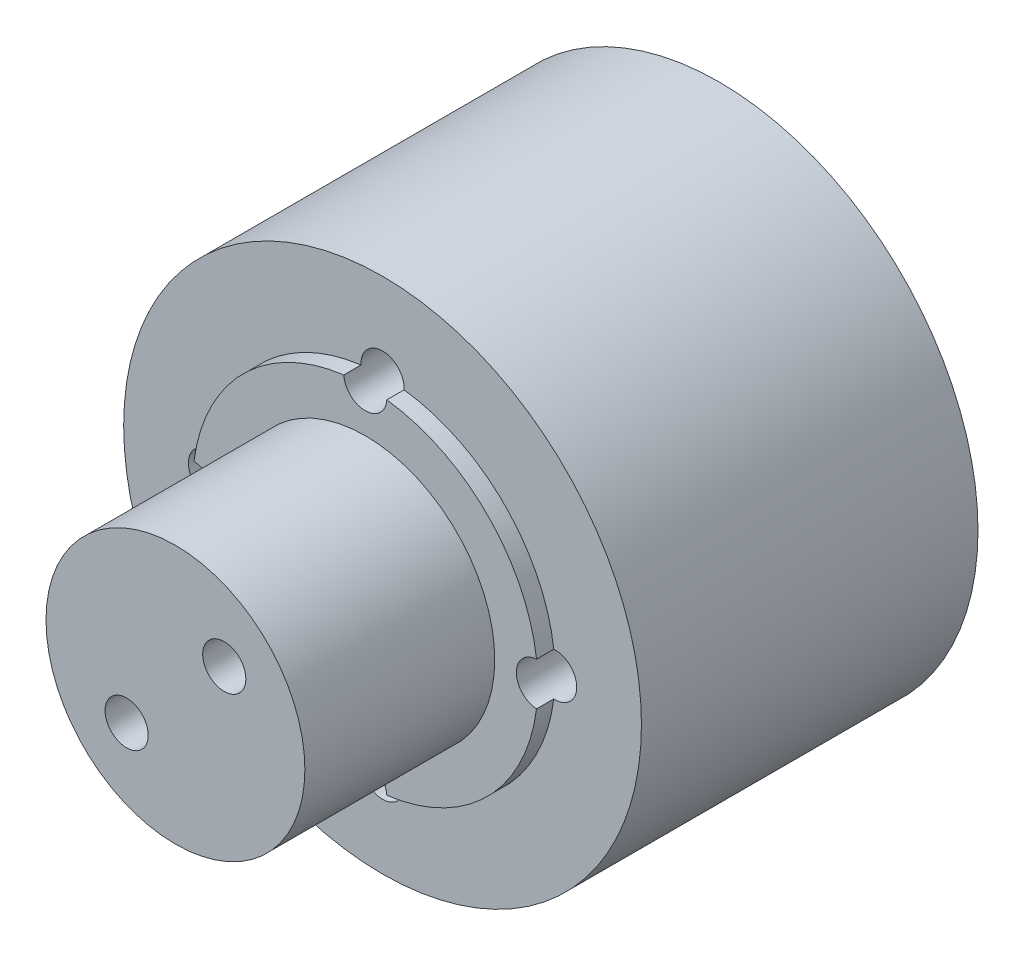
SolidWorks part; units mm, degrees
ref_plane "Спереди" through (0, 0, 0) normal (0, 0, 1) x (1, 0, 0)
ref_plane "Сверху" through (0, 0, 0) normal (0, 1, 0) x (1, 0, 0)
ref_plane "Справа" through (0, 0, 0) normal (1, 0, 0) x (0, 0, -1)
sketch "Эскиз1" plane through (0, 0, 0) normal (0, 0, 1) x (1, 0, 0)
  circle A0 centre (0, 0) radius 15
  dimension "D1" = 30
extrude "Бобышка-Вытянуть1" add sketch "Эскиз1" along normal blind 19.5
sketch "Эскиз2" plane through (0, 0, 19.5) normal (0, 0, 1) x (1, 0, 0)
  circle A0 centre (0, 0) radius 10
  dimension "D1" = 20
extrude "Бобышка-Вытянуть2" add sketch "Эскиз2" along normal blind 1
sketch "Эскиз3" plane through (0, 0, 20.5) normal (0, 0, 1) x (1, 0, 0)
  circle A0 centre (0, 0) radius 7.5
  dimension "D1" = 15
extrude "Бобышка-Вытянуть3" add sketch "Эскиз3" along normal blind 11
sketch "Эскиз4" plane through (0, 0, 0) normal (0, 0, -1) x (-1, 0, 0)
  line L0 (0, 15) -> (0, -15) construction
  line L1 (-15, 0) -> (15, 0) construction
  circle A0 centre (0, 0) radius 15 construction
  circle A1 centre (0, 0) radius 10 construction
  dimension "D1" = 20
hole_wizard "Отверстие обработанное метчиком M3x0.52" positions "Эскиз6" profile "Эскиз5" tap size "M3x0.5" standard "Ansi Metric" end condition through all
sketch "Эскиз6" plane through (0, 0, 0) normal (0, 0, -1) x (-1, 0, 0)
  line L0 (0, 15) -> (0, -15) construction
  line L1 (-15, 0) -> (15, 0) construction
  circle A0 centre (0, 0) radius 10 construction
  point P0 (0, 10)
  point P6 (10, 0)
  point P10 (-10, 0)
  point P12 (0, -10)
sketch "Эскиз5" plane through (0, 10, 0) normal (1, 0, 0) x (0, 1, 0)
  line L0 (0, 0) -> (0, 31.5)
  line L1 (0, 31.5) -> (1.25, 31.5)
  line L2 (1.25, 31.5) -> (1.25, 0)
  line L5 (1.25, 0) -> (0, 0)
  line L11 (0, -6.35) -> (0, 107.95) construction
  dimension "Диаметр проходного сверла" = 2.5
  dimension "Глубина проходного сверла" = 31.5
cosmetic thread "Отверстие резьбы1" parameters "D2"=3
cosmetic thread "Отверстие резьбы2" parameters "D2"=3
cosmetic thread "Отверстие резьбы3" parameters "D2"=3
cosmetic thread "Отверстие резьбы4" parameters "D2"=3
sketch "Эскиз7" plane through (0, 0, 31.5) normal (0, 0, 1) x (1, 0, 0)
  line L0 (2.8284, 2.8284) -> (-2.8284, -2.8284) construction
  line L1 (15, 0) -> (-15, 0) construction
  line L2 (-2.8284, 2.8284) -> (2.8284, -2.8284) construction
  circle A0 centre (0, 0) radius 4 construction
  dimension "D1" = 8
  dimension "D2" = 45
hole_wizard "Отверстие обработанное метчиком M3x0.51" positions "Эскиз9" profile "Эскиз8" tap size "M3x0.5" standard "Ansi Metric"
sketch "Эскиз9" plane through (0, 0, 31.5) normal (0, 0, 1) x (1, 0, 0)
  point P0 (-2.8284, -2.8284)
  point P3 (2.8284, 2.8284)
cosmetic thread "Отверстие резьбы5" parameters "D1"=8, "D2"=3
cosmetic thread "Отверстие резьбы6" parameters "D1"=8, "D2"=3
sketch "Эскиз8" plane through (-2.8284, -2.8284, 31.5) normal (1, 0, 0) x (0, -1, 0)
  line L0 (0, 0) -> (0, 8.7511)
  line L1 (0, 8.7511) -> (1.25, 8)
  line L2 (1.25, 8) -> (1.25, 0)
  line L5 (1.25, 0) -> (0, 0)
  line L10 (0, 8.7511) -> (-1.25, 8) construction
  line L11 (0, -6.35) -> (0, 107.95) construction
  dimension "Диаметр сверла" = 2.5
  dimension "Глубина сверла" = 8
  dimension "Угол заточки сверла" = 118
